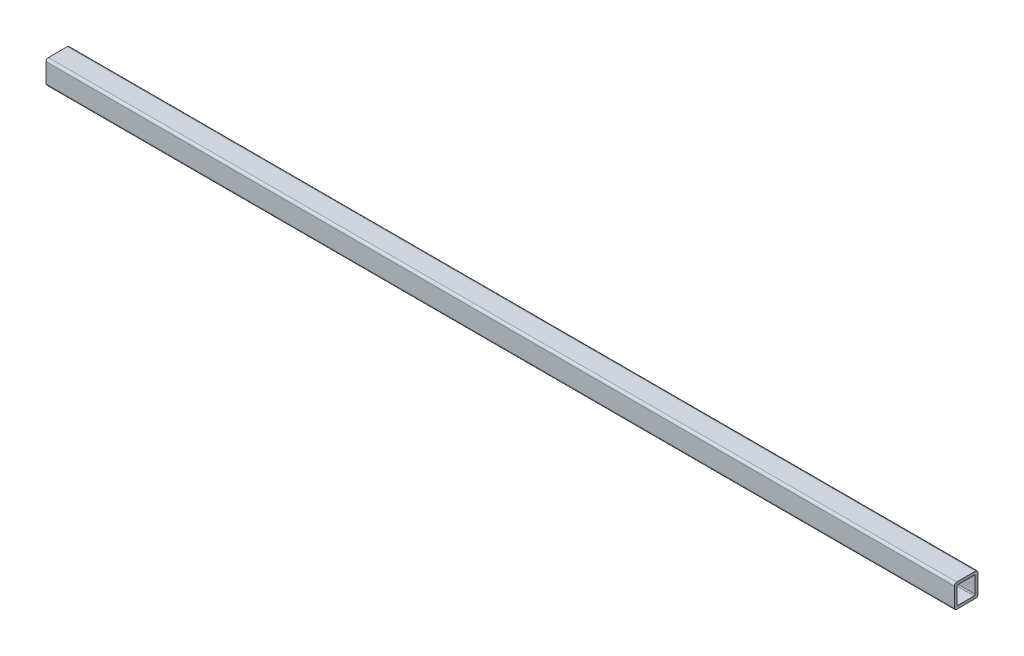
SolidWorks part; units mm, degrees
ref_plane "Front Plane" through (0, 0, 0) normal (0, 0, 1) x (1, 0, 0)
ref_plane "Top Plane" through (0, 0, 0) normal (0, 1, 0) x (1, 0, 0)
ref_plane "Right Plane" through (0, 0, 0) normal (1, 0, 0) x (0, 0, -1)
sketch "Sketch3" plane through (0, 0, 0) normal (1, 0, 0) x (0, 0, -1)
  line L1 (-12.7, 12.7) -> (12.7, 12.7)
  line L2 (-12.7, 12.7) -> (-12.7, -12.7)
  line L3 (-12.7, -12.7) -> (12.7, -12.7)
  line L4 (12.7, 12.7) -> (12.7, -12.7)
  line L5 (-12.7, 12.7) -> (12.7, -12.7) construction
  line L6 (-12.7, -12.7) -> (12.7, 12.7) construction
  line L7 (-9.652, -9.652) -> (9.652, -9.652)
  line L8 (-9.652, -9.652) -> (-9.652, 9.652)
  line L9 (-9.652, 9.652) -> (9.652, 9.652)
  line L10 (9.652, -9.652) -> (9.652, 9.652)
  line L11 (-9.652, -9.652) -> (9.652, 9.652) construction
  line L12 (-9.652, 9.652) -> (9.652, -9.652) construction
  point P0 (0, 0)
  point P6 (0, 0)
  dimension "D1" = 25.4
  dimension "D2" = 19.304
  dimension "D3" = 19.304
  dimension "D4" = 25.4
extrude "Boss-Extrude1" add sketch "Sketch3" against normal blind 974.6
fillet "Fillet1" radius 2.5 4 edges at (-487.3, -12.7, -12.7) (-487.3, -12.7, 12.7) (-487.3, 12.7, -12.7) (-487.3, 12.7, 12.7)
fillet "Fillet2" radius 1 4 edges at (-487.3, -9.652, -9.652) (-487.3, 9.652, -9.652) (-487.3, 9.652, 9.652) (-487.3, -9.652, 9.652)
